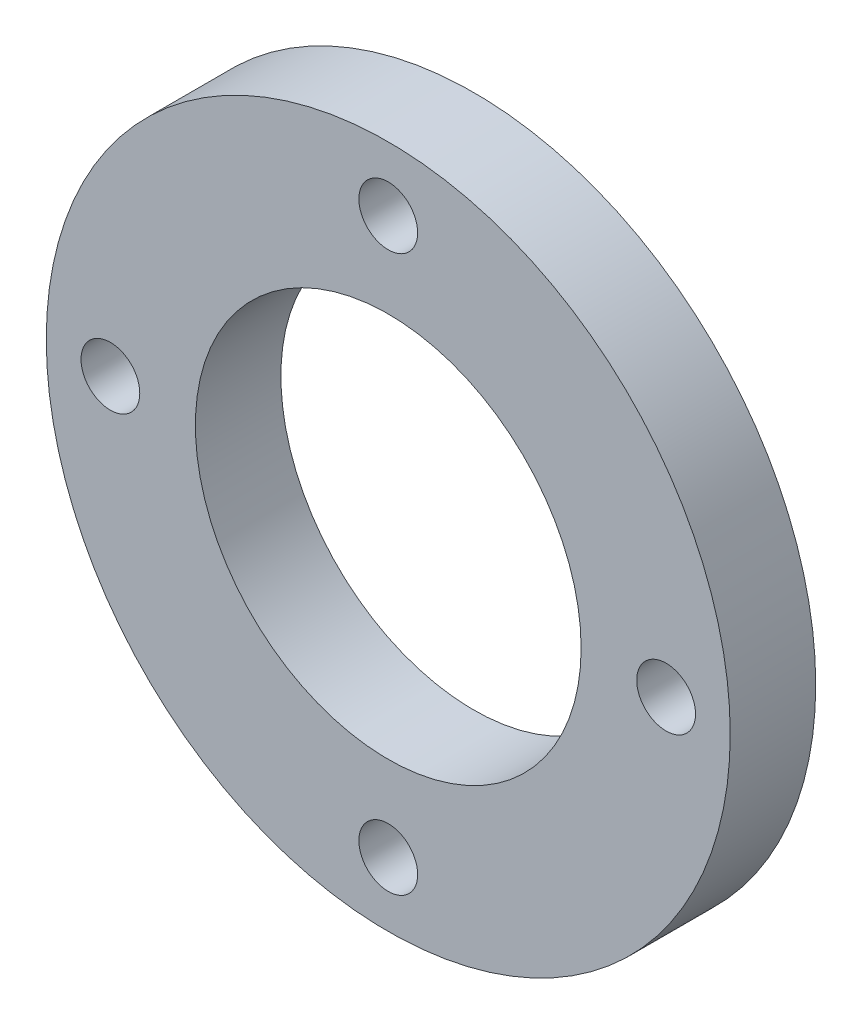
SolidWorks part; units mm, degrees
material "6061 Alloy"
ref_plane "Front Plane" through (0, 0, 0) normal (0, 0, 1) x (1, 0, 0)
ref_plane "Top Plane" through (0, 0, 0) normal (0, 1, 0) x (1, 0, 0)
ref_plane "Right Plane" through (0, 0, 0) normal (1, 0, 0) x (0, 0, -1)
sketch "Sketch1" plane through (0, 0, 0) normal (0, 0, 1) x (1, 0, 0)
  line L0 (-41.275, 0) -> (41.275, 0) construction
  line L1 (0, 41.275) -> (0, -41.275) construction
  circle A0 centre (0, 0) radius 50.8
  circle A1 centre (0, 0) radius 28.6512
  circle A2 centre (0, 0) radius 41.275 construction
  circle A3 centre (0, 41.275) radius 4.3656
  circle A4 centre (41.275, 0) radius 4.3656
  circle A5 centre (0, -41.275) radius 4.3656
  circle A6 centre (-41.275, 0) radius 4.3656
  dimension "D1" = 101.6
  dimension "D2" = 57.3024
  dimension "D3" = 82.55
  dimension "D4" = 8.7312
extrude "Boss-Extrude1" add sketch "Sketch1" along normal blind 12.7
